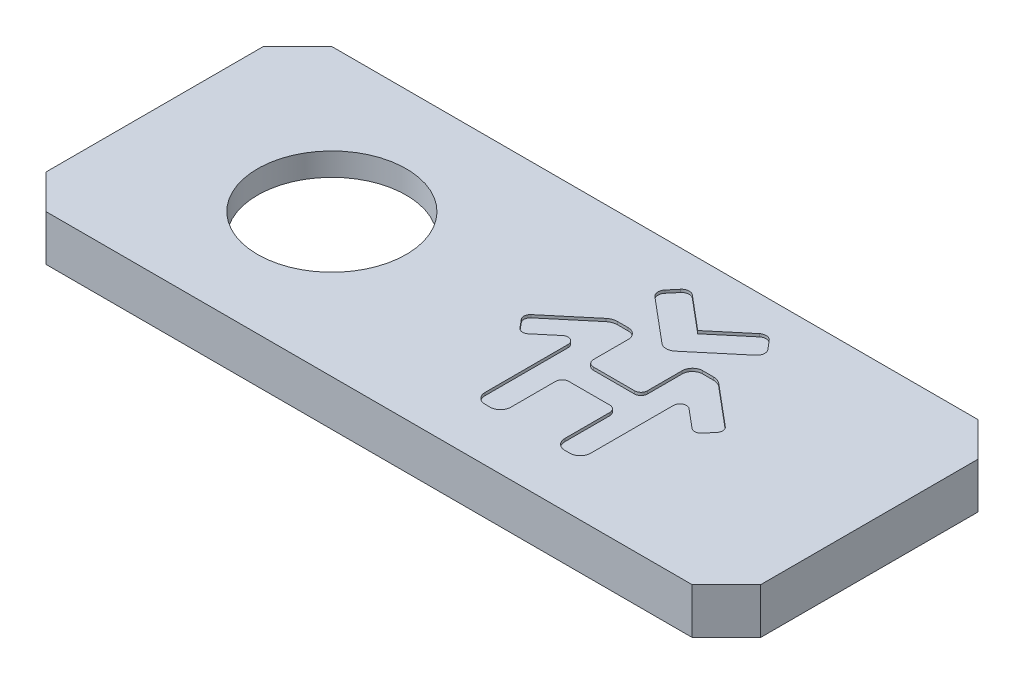
SolidWorks part; units mm, degrees
ref_plane "Спереди" through (0, 0, 0) normal (0, 0, 1) x (1, 0, 0)
ref_plane "Сверху" through (0, 0, 0) normal (0, 1, 0) x (1, 0, 0)
ref_plane "Справа" through (0, 0, 0) normal (1, 0, 0) x (0, 0, -1)
sketch "Эскиз1" plane through (0, 0, 0) normal (0, 1, 0) x (1, 0, 0)
  line L0 (25.8931, 8.2346) -> (-15.6069, 8.2346)
  line L1 (-15.0089, -13.7654) -> (26.4911, -13.7654)
  line L2 (-24.9069, -8.7654) -> (-15.0089, -13.7654)
  line L3 (35.5931, -12.2654) -> (35.5931, 6.7346)
  line L4 (35.5931, 6.7346) -> (32.5931, 9.7346)
  line L5 (32.5931, 9.7346) -> (-23.9069, 9.7346)
  line L6 (-23.9069, 9.7346) -> (-26.9069, 6.7346)
  line L7 (-26.9069, 6.7346) -> (-26.9069, -12.2654)
  line L8 (-26.9069, -12.2654) -> (-23.9069, -15.2654)
  line L9 (-23.9069, -15.2654) -> (32.5931, -15.2654)
  line L10 (32.5931, -15.2654) -> (35.5931, -12.2654)
  line L11 (-24.9069, 2.2346) -> (-24.9069, -8.7654)
  line L12 (-15.6069, 8.2346) -> (-24.9069, 2.2346)
  line L14 (26.4911, -13.7654) -> (33.5931, -10.2654)
  line L15 (33.5931, -10.2654) -> (33.5931, 4.7346)
  line L16 (33.5931, 4.7346) -> (32.5963, 5.1877)
  line L17 (30.1447, 6.3021) -> (25.8931, 8.2346)
  circle A0 centre (-22.9069, -11.7654) radius 1.45
  arc A1 (32.5963, 5.1877) -> (30.1447, 6.3021) centre (31.5931, 6.2346) ccw
extrude "Бобышка-Вытянуть1" add sketch "Эскиз1" along normal blind 2
sketch "Эскиз2" plane through (0, 2, 0) normal (0, 1, 0) x (1, 0, 0)
  line L8 (32.5931, -15.2654) -> (35.5931, -12.2654)
  line L9 (35.5931, -12.2654) -> (35.5931, 6.7346)
  line L10 (35.5931, 6.7346) -> (32.5931, 9.7346)
  line L11 (32.5931, 9.7346) -> (-23.9069, 9.7346)
  line L12 (-23.9069, 9.7346) -> (-26.9069, 6.7346)
  line L13 (-26.9069, 6.7346) -> (-26.9069, -12.2654)
  line L14 (-26.9069, -12.2654) -> (-23.9069, -15.2654)
  line L15 (-23.9069, -15.2654) -> (32.5931, -15.2654)
  line L16 (32.5931, -15.2654) -> (35.5931, -12.2654)
  line L17 (35.5931, -12.2654) -> (35.5931, 6.7346)
  line L18 (35.5931, 6.7346) -> (32.5931, 9.7346)
  line L19 (32.5931, 9.7346) -> (-23.9069, 9.7346)
  line L20 (-23.9069, 9.7346) -> (-26.9069, 6.7346)
  line L21 (-26.9069, 6.7346) -> (-26.9069, -12.2654)
  line L22 (-26.9069, -12.2654) -> (-23.9069, -15.2654)
  line L23 (-23.9069, -15.2654) -> (32.5931, -15.2654)
  dimension "D1" = 0
extrude "Бобышка-Вытянуть2" add sketch "Эскиз2" along normal blind 2
sketch "Эскиз3" plane through (0, 4, 0) normal (0, 1, 0) x (1, 0, 0)
  line L0 (32.5931, 9.7346) -> (-23.9069, 9.7346) construction
  line L1 (-26.9069, 6.7346) -> (-26.9069, -12.2654) construction
  circle A0 centre (-11.4069, -2.7654) radius 6.5
  dimension "D3" = 13
  dimension "D1" = 12.5
  dimension "D2" = 15.5
extrude "Вырез-Вытянуть1" cut sketch "Эскиз3" against normal blind 2
sketch "Эскиз4" plane through (0, 2, 0) normal (0, -1, 0) x (1, 0, 0)
  circle A0 centre (31.5931, -6.2346) radius 1.45
  circle A1 centre (-22.9069, 11.7654) radius 1.45
  circle A2 centre (-22.9069, 11.7654) radius 1.45
  arc A3 (30.1447, -6.3021) -> (32.5963, -5.1877) centre (31.5931, -6.2346) ccw construction
  dimension "D1" = 0
extrude "Вырез-Вытянуть2" cut sketch "Эскиз4" against normal blind 1
sketch "Эскиз5" plane through (0, 4, 0) normal (0, 1, 0) x (1, 0, 0)
  line L0 (8.9806, -2.501) -> (8.9806, -9.7584)
  line L1 (9.8806, -10.6584) -> (10.3306, -10.6584)
  line L2 (11.2306, -9.7584) -> (11.2306, -5.8279)
  line L3 (11.7931, -5.2654) -> (15.3931, -5.2654)
  line L4 (9.3901, 1.4016) -> (10.3306, 1.4016)
  line L5 (11.2306, 0.5016) -> (11.2306, -2.5359)
  line L6 (13.5931, -451.9609) -> (13.5931, 22048.0391) construction
  line L7 (11.7931, -3.0984) -> (15.3931, -3.0984)
  line L8 (8.6669, 1.1384) -> (5.1025, -1.8525)
  line L9 (5.0332, -2.6449) -> (5.6377, -3.3654)
  line L10 (6.4302, -3.4348) -> (8.0565, -2.0701)
  line L11 (20.756, -3.4348) -> (19.1297, -2.0701)
  line L12 (22.153, -2.6449) -> (21.5485, -3.3654)
  line L13 (18.5193, 1.1384) -> (22.0837, -1.8525)
  line L14 (15.9556, 0.5016) -> (15.9556, -2.5359)
  line L15 (17.7961, 1.4016) -> (16.8556, 1.4016)
  line L16 (15.9556, -9.7584) -> (15.9556, -5.8279)
  line L17 (17.3056, -10.6584) -> (16.8556, -10.6584)
  line L18 (18.2056, -2.501) -> (18.2056, -9.7584)
  line L19 (13.5931, 4.2263) -> (10.665, 6.6833)
  line L20 (9.714, 6.6001) -> (9.088, 5.854)
  line L21 (9.1712, 4.9031) -> (13.0146, 1.6781)
  line L22 (18.015, 4.9031) -> (14.1716, 1.6781)
  line L23 (13.5931, 4.2263) -> (16.5212, 6.6833)
  line L24 (17.4722, 6.6001) -> (18.0982, 5.854)
  line L25 (35.5931, -12.2654) -> (35.5931, 6.7346) construction
  line L26 (-23.9069, -15.2654) -> (32.5931, -15.2654) construction
  arc A0 (8.9806, -9.7584) -> (9.8806, -10.6584) centre (9.8806, -9.7584) ccw
  arc A1 (10.3306, -10.6584) -> (11.2306, -9.7584) centre (10.3306, -9.7584) ccw
  arc A2 (11.2306, 0.5016) -> (10.3306, 1.4016) centre (10.3306, 0.5016) ccw
  arc A3 (9.3901, 1.4016) -> (8.6669, 1.1384) centre (9.3901, 0.2766) ccw
  arc A4 (11.7931, -5.2654) -> (11.2306, -5.8279) centre (11.7931, -5.8279) ccw
  arc A5 (11.7931, -3.0984) -> (11.2306, -2.5359) centre (11.7931, -2.5359) cw
  arc A6 (8.9806, -2.501) -> (8.0565, -2.0701) centre (8.4181, -2.501) ccw
  arc A7 (6.4302, -3.4348) -> (5.6377, -3.3654) centre (6.0686, -3.0039) cw
  arc A8 (5.1025, -1.8525) -> (5.0332, -2.6449) centre (5.4641, -2.2834) ccw
  arc A9 (22.0837, -1.8525) -> (22.153, -2.6449) centre (21.7221, -2.2834) cw
  arc A10 (20.756, -3.4348) -> (21.5485, -3.3654) centre (21.1176, -3.0039) ccw
  arc A11 (18.2056, -2.501) -> (19.1297, -2.0701) centre (18.7681, -2.501) cw
  arc A12 (15.3931, -3.0984) -> (15.9556, -2.5359) centre (15.3931, -2.5359) ccw
  arc A13 (15.3931, -5.2654) -> (15.9556, -5.8279) centre (15.3931, -5.8279) cw
  arc A14 (17.7961, 1.4016) -> (18.5193, 1.1384) centre (17.7961, 0.2766) cw
  arc A15 (15.9556, 0.5016) -> (16.8556, 1.4016) centre (16.8556, 0.5016) cw
  arc A16 (16.8556, -10.6584) -> (15.9556, -9.7584) centre (16.8556, -9.7584) cw
  arc A17 (18.2056, -9.7584) -> (17.3056, -10.6584) centre (17.3056, -9.7584) cw
  arc A18 (9.1712, 4.9031) -> (9.088, 5.854) centre (9.6051, 5.4201) cw
  arc A19 (10.665, 6.6833) -> (9.714, 6.6001) centre (10.2311, 6.1662) ccw
  arc A20 (16.5212, 6.6833) -> (17.4722, 6.6001) centre (16.9551, 6.1662) cw
  arc A21 (18.015, 4.9031) -> (18.0982, 5.854) centre (17.5811, 5.4201) ccw
  arc A22 (14.1716, 1.6781) -> (13.0146, 1.6781) centre (13.5931, 2.3675) cw
  point P35 (13.5931, -5.2654)
  point P36 (13.5931, -3.0984)
  point P61 (16.9326, -1.414)
  point P62 (10.3736, -2.2984)
  point P63 (10.3736, -4.4584)
  point P64 (12.6236, 2.2016)
  point P65 (10.3736, 2.2016)
  point P66 (10.3736, -9.8584)
  point P67 (12.6236, -9.8584)
  point P79 (10.7015, 7.2838)
  point P80 (12.1478, 5.5602)
  dimension "D3" = 0.9
  dimension "D4" = 1.125
  dimension "D6" = 0.675
  dimension "D7" = 0.9
  dimension "D8" = 0.5625
  dimension "D1" = 2.3625
  dimension "D2" = 50
  dimension "D5" = 50
  dimension "D9" = 22
  dimension "D10" = 2.3239
  dimension "D11" = 10
  dimension "D12" = 2.167
  dimension "D13" = 7.3247
  dimension "D14" = 3.0375
  dimension "D15" = 2.25
  dimension "D16" = 2.0655
  dimension "D17" = 2.123
  dimension "D18" = 4.653
extrude "Вырез-Вытянуть3" cut sketch "Эскиз5" against normal blind 0.25
